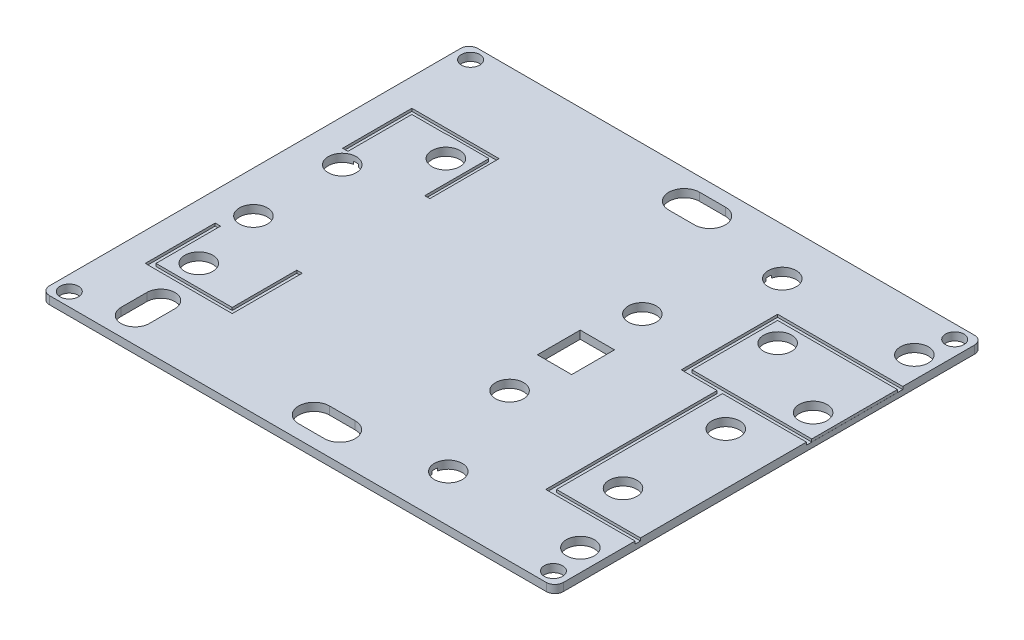
SolidWorks part; units mm, degrees
material "PE High Density Film"
ref_plane "Front Plane" through (0, 0, 0) normal (0, 0, 1) x (1, 0, 0)
ref_plane "Top Plane" through (0, 0, 0) normal (0, 1, 0) x (1, 0, 0)
ref_plane "Right Plane" through (0, 0, 0) normal (1, 0, 0) x (0, 0, -1)
sketch "Sketch1" plane through (0, 0, 0) normal (0, 1, 0) x (1, 0, 0)
  line L1 (-76.2, 63.5) -> (76.2, 63.5)
  line L2 (-76.2, 63.5) -> (-76.2, -63.5)
  line L3 (-76.2, -63.5) -> (76.2, -63.5)
  line L4 (76.2, 63.5) -> (76.2, -63.5)
  line L5 (-76.2, 63.5) -> (76.2, -63.5) construction
  line L6 (-76.2, -63.5) -> (76.2, 63.5) construction
  point P0 (0, 0)
  dimension "D1" = 127
  dimension "D2" = 152.4
extrude "Boss-Extrude1" add sketch "Sketch1" along normal blind 2.3622
fillet "Fillet1" radius 2.54 4 edges at (76.2, 1.1811, 63.5) (76.2, 1.1811, -63.5) (-76.2, 1.1811, -63.5) (-76.2, 1.1811, 63.5)
sketch "Sketch9" plane through (0, 0, 0) normal (0, -1, 0) x (1, 0, 0)
  circle A0 centre (60.8584, 27.94) radius 4.15
  circle A1 centre (60.8584, -2.54) radius 4.15
  dimension "D1" = 8.3
  dimension "D2" = 8.3
extrude "Cut-Extrude8" cut sketch "Sketch9" against normal through all
sketch "Sketch12" plane through (0, 0, 0) normal (0, -1, 0) x (1, 0, 0)
  line L0 (-3.81, 54.8882) -> (3.81, 54.8882) construction
  line L1 (-3.81, 59.4656) -> (3.81, 59.4656)
  line L2 (-3.81, 50.3108) -> (3.81, 50.3108)
  line L3 (76.2, 60.96) -> (76.2, -60.96) construction
  arc A0 (-3.81, 59.4656) -> (-3.81, 50.3108) centre (-3.81, 54.8882) ccw
  arc A1 (3.81, 50.3108) -> (3.81, 59.4656) centre (3.81, 54.8882) ccw
  point P2 (0, 54.8882)
  dimension "D1" = 7.62
  dimension "D2" = 76.2
extrude "Cut-Extrude11" cut sketch "Sketch12" against normal through all
mirror "Mirror3" about plane through (0, 0, 0) normal (0, 0, 1) of "Cut-Extrude11"
sketch "Sketch13" plane through (0, 0, 0) normal (0, -1, 0) x (-1, 0, 0)
  line L0 (55.88, -48.26) -> (55.88, -55.88) construction
  line L1 (60.0529, -48.26) -> (60.0529, -55.88)
  line L2 (51.7071, -48.26) -> (51.7071, -55.88)
  line L3 (73.66, -63.5) -> (-73.66, -63.5) construction
  line L4 (76.2, 61.0698) -> (76.2, -60.8502) construction
  arc A0 (60.0529, -48.26) -> (51.7071, -48.26) centre (55.88, -48.26) ccw
  arc A1 (51.7071, -55.88) -> (60.0529, -55.88) centre (55.88, -55.88) ccw
  point P2 (55.88, -52.07)
  dimension "D1" = 7.62
  dimension "D2" = 7.62
  dimension "D3" = 20.32
extrude "Cut-Extrude12" cut sketch "Sketch13" against normal through all
sketch "Sketch16" plane through (0, 0, 0) normal (0, -1, 0) x (-1, 0, 0)
  circle A0 centre (-69.5999, 19.7043) radius 4.15
  circle A1 centre (-46.5226, 32.2642) radius 4.15
  dimension "D1" = 8.3
extrude "Cut-Extrude14" cut sketch "Sketch16" against normal through all
sketch "Sketch17" plane through (0, 0, 0) normal (0, -1, 0) x (1, 0, 0)
  circle A0 centre (71.7948, 59.5104) radius 2.7305
  dimension "D1" = 5.461
extrude "Cut-Extrude16" cut sketch "Sketch17" against normal through all
mirror "Mirror6" about plane through (0, 0, 0) normal (1, 0, 0) of "Cut-Extrude16"
mirror "Mirror7" about plane through (0, 0, 0) normal (0, 0, 1) of "Mirror6", "Cut-Extrude16"
sketch "Sketch26" plane through (0, 2.3622, 0) normal (0, 1, 0) x (1, 0, 0)
  line L1 (24.0446, 6.35) -> (13.8846, 6.35)
  line L2 (24.0446, 6.35) -> (24.0446, -6.35)
  line L3 (24.0446, -6.35) -> (13.8846, -6.35)
  line L4 (13.8846, 6.35) -> (13.8846, -6.35)
extrude "Cut-Extrude26" cut sketch "Sketch26" against normal through all
sketch "Sketch27" plane through (0, 0, 0) normal (0, -1, 0) x (1, 0, 0)
  circle A0 centre (-59.8314, 33.0604) radius 4.15
  circle A1 centre (-50.0917, -30.48) radius 4.15
  dimension "D1" = 8.3
extrude "Cut-Extrude27" cut sketch "Sketch27" against normal through all
sketch "Sketch29" plane through (0, 2.3622, 0) normal (0, 1, 0) x (1, 0, 0)
  circle A0 centre (18.9646, 19.6812) radius 4.15
  circle A1 centre (18.9646, -19.6812) radius 4.15
  dimension "D1" = 8.3
extrude "Cut-Extrude28" cut sketch "Sketch29" against normal through all
sketch "Sketch30" plane through (0, 2.3622, 0) normal (0, 1, 0) x (1, 0, 0)
  line L0 (75.66, -63.5) -> (-73.66, -63.5) construction
  line L2 (-73.66, -63.5) -> (73.66, -63.5) construction
  circle A0 centre (69.8033, -49.53) radius 4.15
  circle A1 centre (30.6352, -49.53) radius 4.15
  dimension "D1" = 8.3
  dimension "D2" = 13.97
  dimension "D3" = 13.97
extrude "Cut-Extrude29" cut sketch "Sketch30" against normal through all
mirror "Mirror8" about plane through (0, 0, 0) normal (0, 0, 1) of "Cut-Extrude29"
sketch "Sketch31" plane through (0, 2.3622, 0) normal (0, 1, 0) x (1, 0, 0)
  circle A0 centre (-63.8948, -12.7955) radius 4.15
  circle A1 centre (-63.8948, 13.5496) radius 4.15
  dimension "D1" = 8.3
extrude "Cut-Extrude30" cut sketch "Sketch31" against normal through all
sketch "Sketch32" plane through (0, 2.3622, 0) normal (0, 1, 0) x (1, 0, 0)
  line L1 (-66.1553, -39.4364) -> (-43.5336, -39.4364)
  line L2 (-66.1553, -39.4364) -> (-66.1553, -20.2936)
  line L3 (-66.1553, -20.2936) -> (-43.5336, -20.2936)
  line L4 (-43.5336, -39.4364) -> (-43.5336, -20.2936)
  line L5 (-56.2335, -20.3456) -> (-43.7678, -20.3456)
  line L6 (-56.2335, -20.3456) -> (-56.2335, 36.856)
  line L7 (-56.2335, 36.856) -> (-43.7678, 36.856)
  line L8 (-43.7678, -20.3456) -> (-43.7678, 36.856)
  line L9 (-66.4676, 36.7629) -> (-43.6897, 36.7629)
  line L10 (-66.4676, 36.7629) -> (-66.4676, 17.8061)
  line L11 (-66.4676, 17.8061) -> (-43.6897, 17.8061)
  line L12 (-43.6897, 36.7629) -> (-43.6897, 17.8061)
  line L13 (-67.7428, -41.0239) -> (-41.9461, -41.0239)
  line L14 (-67.7428, -41.0239) -> (-67.7428, -20.2936)
  line L15 (-67.7428, -20.2936) -> (-41.9461, -20.2936)
  line L16 (-41.9461, -41.0239) -> (-41.9461, -20.2936)
  line L17 (-42.1803, 38.3504) -> (-68.0551, 38.3504)
  line L18 (-42.1803, 38.3504) -> (-42.1803, 17.8061)
  line L19 (-42.1803, 17.8061) -> (-68.0551, 17.8061)
  line L20 (-68.0551, 38.3504) -> (-68.0551, 17.8061)
  dimension "D1" = 1.5875
  dimension "D2" = 1.5875
  dimension "D3" = 0
  dimension "D4" = 1.5875
  dimension "D5" = 1.5875
  dimension "D6" = 1.5875
  dimension "D7" = 1.5875
  dimension "D8" = 0
extrude "Cut-Extrude31" cut sketch "Sketch32" against normal blind 0.7937 contours L17 L20 L19 L10 L9 L6 L7 L8 L12 L18 | L13 L16 L15 L4 L1 L2 L14
sketch "Sketch33" plane through (0, 2.3622, 0) normal (0, 1, 0) x (1, 0, 0)
  line L0 (76.2, -60.96) -> (76.2, 60.96) construction
  line L1 (40.6697, 12.7135) -> (76.1849, 12.7135)
  line L2 (40.6697, 12.7135) -> (40.6697, 38.1044)
  line L3 (40.6697, 38.1044) -> (76.1849, 38.1044)
  line L4 (76.1849, 12.7135) -> (76.1849, 38.1044)
  line L5 (51.2978, 14.064) -> (76.2, 14.064)
  line L6 (51.2978, 14.064) -> (51.2978, -38.1)
  line L7 (51.2978, -38.1) -> (76.2, -38.1)
  line L8 (76.2, 14.064) -> (76.2, -38.1)
  line L9 (76.2, -38.1) -> (71.12, -38.1) construction
  line L11 (49.7103, -39.6875) -> (76.2, -39.6875)
  line L12 (49.7103, -39.6875) -> (49.7103, 14.064)
  line L13 (49.7103, 14.064) -> (76.2, 14.064)
  line L14 (76.2, -39.6875) -> (76.2, 14.064)
  line L15 (39.0822, 11.126) -> (76.2, 11.126)
  line L16 (39.0822, 11.126) -> (39.0822, 39.6919)
  line L17 (39.0822, 39.6919) -> (76.2, 39.6919)
  line L18 (76.2, 11.126) -> (76.2, 39.6919)
  dimension "D1" = 1.5875
  dimension "D2" = 1.5875
  dimension "D3" = 1.5875
  dimension "D4" = 1.5875
  dimension "D5" = 1.5875
extrude "Cut-Extrude32" cut sketch "Sketch33" against normal blind 0.7937 contours L15 L12 L11 L14 L7 L6 | L6 L15 L8 L5 L4 L1 | L12 L15 L6 L1 | L5 L18 L17 L16 L15 L12 L1 L2 L3 L4
sketch "Sketch34" plane through (0, 0, 0) normal (0, -1, 0) x (1, 0, 0)
  line L1 (-76.2, -19.2145) -> (-51.5674, -19.2145)
  line L2 (-76.2, -19.2145) -> (-76.2, 18.4605)
  line L3 (-76.2, 18.4605) -> (-51.5674, 18.4605)
  line L4 (-51.5674, -19.2145) -> (-51.5674, 18.4605)
  line L5 (-74.6125, -17.627) -> (-53.1549, -17.627)
  line L6 (-74.6125, -17.627) -> (-74.6125, 16.873)
  line L7 (-74.6125, 16.873) -> (-53.1549, 16.873)
  line L8 (-53.1549, -17.627) -> (-53.1549, 16.873)
extrude "Cut-Extrude33" cut sketch "Sketch34" against normal blind 0.7937
sketch "Sketch36" plane through (0, 0, 0) normal (0, -1, 0) x (1, 0, 0)
  line L1 (26.5712, 44.45) -> (75.2732, 44.45)
  line L2 (26.5712, 44.45) -> (26.5712, 54.61)
  line L3 (26.5712, 54.61) -> (75.2732, 54.61)
  line L4 (75.2732, 44.45) -> (75.2732, 54.61)
  line L5 (24.9837, 42.8625) -> (75.2732, 42.8625)
  line L6 (24.9837, 42.8625) -> (24.9837, 56.1975)
  line L7 (24.9837, 56.1975) -> (75.2732, 56.1975)
  line L8 (75.2732, 42.8625) -> (75.2732, 56.1975)
  circle M15 centre (30.6352, 49.53) radius 4.15
  dimension "D1" = 1.5875
  dimension "D2" = 1.5875
  dimension "D3" = 1.5875
  dimension "D4" = 0
extrude "Cut-Extrude34" cut sketch "Sketch36" against normal blind 0.7937 contours L5 L8 L1 L2 L3 L7 L6 M15
mirror "Mirror9" about plane through (0, 0, 0) normal (0, 0, 1) of "Cut-Extrude34"
